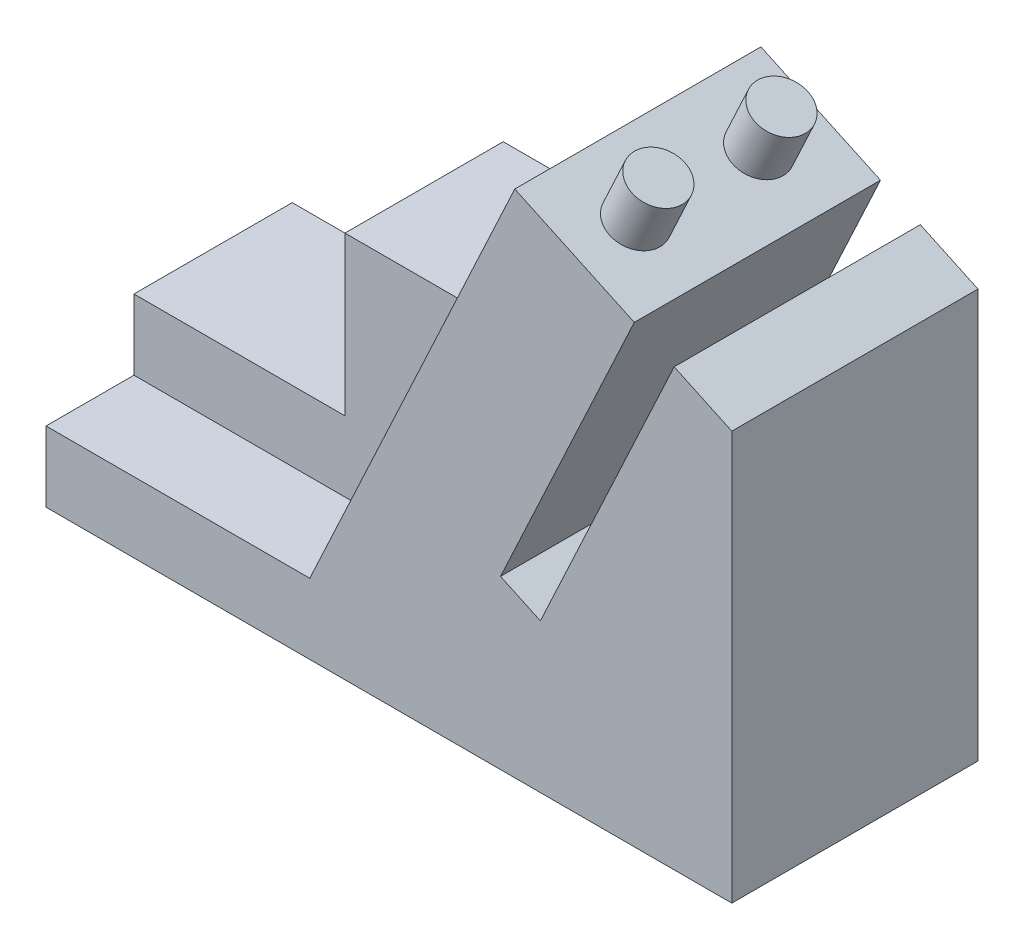
SolidWorks part; units mm, degrees
ref_plane "Płaszczyzna przednia" through (0, 0, 0) normal (0, 0, 1) x (1, 0, 0)
ref_plane "Płaszczyzna górna" through (0, 0, 0) normal (0, 1, 0) x (1, 0, 0)
ref_plane "Płaszczyzna prawa" through (0, 0, 0) normal (1, 0, 0) x (0, 0, -1)
sketch "Szkic1" plane through (0, 0, 0) normal (0, 0, 1) x (1, 0, 0)
  line L0 (0, 0) -> (78, 0)
  line L1 (78, 0) -> (78, 46.4894)
  line L2 (78, 46.4894) -> (71.4415, 49.5476)
  line L3 (53.3154, 58) -> (30, 8)
  line L4 (30, 8) -> (0, 8)
  line L5 (0, 8) -> (0, 0)
  line L6 (66.91, 51.6607) -> (51.6957, 19.0336)
  line L7 (51.6957, 19.0336) -> (56.2273, 16.9206)
  line L8 (56.2273, 16.9206) -> (71.4415, 49.5476)
  line L9 (66.91, 51.6607) -> (53.3154, 58)
  dimension "D1" = 8
  dimension "D2" = 78
  dimension "D3" = 65
  dimension "D4" = 58
  dimension "D5" = 5
  dimension "D6" = 36
  dimension "D7" = 15
  dimension "D8" = 30
extrude "Dodanie-wyciągnięcie1" add sketch "Szkic1" along normal blind 28
sketch "Szkic2" plane through (31.7377, 68.0618, 0) normal (0.4226, 0.9063, 0) x (0.9063, -0.4226, 0)
  line L0 (23.8083, -28) -> (23.8083, 0) construction
  line L1 (38.8083, -28) -> (23.8083, -28) construction
  line L2 (38.8083, 0) -> (23.8083, 0) construction
  circle A0 centre (31.3083, -7) radius 3
  circle A1 centre (31.3083, -21) radius 3
  point P6 (0, 0)
  point P7 (0, 0)
  dimension "D2" = 6
  dimension "D3" = 6
  dimension "D1" = 7.5
  dimension "D4" = 7
  dimension "D5" = 7
extrude "Dodanie-wyciągnięcie2" add sketch "Szkic2" along normal blind 6
sketch "Szkic3" plane through (0, 0, 0) normal (0, 0, 1) x (1, 0, 0)
  line L0 (0, 8) -> (0, 16)
  line L1 (0, 16) -> (24, 16)
  line L2 (24, 16) -> (24, 34)
  line L3 (24, 34) -> (42.124, 34)
  line L5 (0, 0) -> (78, 0) construction
  line L6 (53.3154, 58) -> (30, 8) construction
  line L7 (0, 8) -> (30, 8)
  line L8 (30, 8) -> (42.124, 34)
  dimension "D1" = 24
  dimension "D2" = 18
  dimension "D3" = 16
extrude "Dodanie-wyciągnięcie3" add sketch "Szkic3" along normal blind 18
